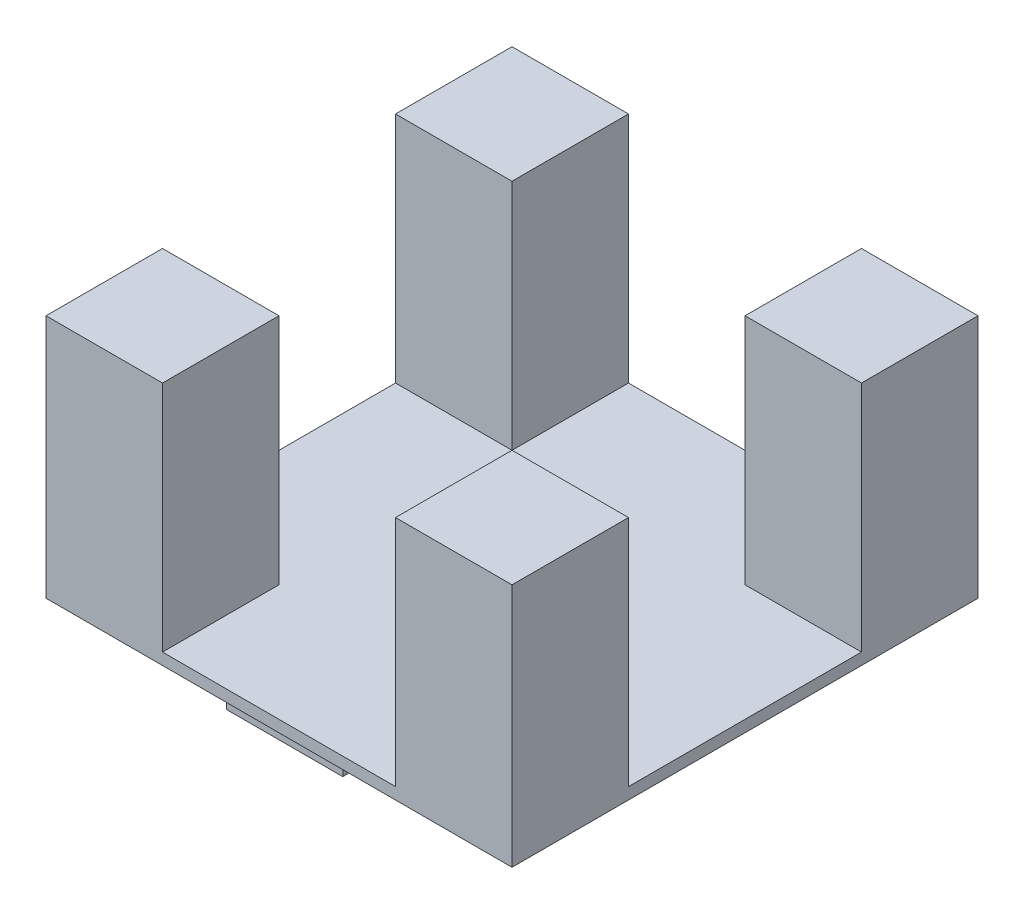
SolidWorks part; units mm, degrees
ref_plane "Front Plane" through (0, 0, 0) normal (0, 0, 1) x (1, 0, 0)
ref_plane "Top Plane" through (0, 0, 0) normal (0, 1, 0) x (1, 0, 0)
ref_plane "Right Plane" through (0, 0, 0) normal (1, 0, 0) x (0, 0, -1)
sketch "Sketch1" plane through (0, 0, 0) normal (0, 1, 0) x (1, 0, 0)
  line L1 (-1000, 1000) -> (1000, 1000)
  line L2 (-1000, 1000) -> (-1000, -1000)
  line L3 (-1000, -1000) -> (1000, -1000)
  line L4 (1000, 1000) -> (1000, -1000)
  line L5 (-1000, 1000) -> (1000, -1000) construction
  line L6 (-1000, -1000) -> (1000, 1000) construction
  point P0 (0, 0)
  dimension "D1" = 2000
  dimension "D2" = 2000
extrude "Boss-Extrude1" add sketch "Sketch1" along normal blind 50
sketch "Sketch2" plane through (0, 50, 0) normal (0, 1, 0) x (1, 0, 0)
  line L1 (-1000, 1000) -> (-500, 1000)
  line L2 (-1000, 1000) -> (-1000, 500)
  line L3 (-1000, 500) -> (-500, 500)
  line L4 (-500, 1000) -> (-500, 500)
  dimension "D1" = 500
  dimension "D2" = 500
extrude "Boss-Extrude2" add sketch "Sketch2" along normal blind 1000
mirror "Mirror1" about plane through (0, 0, 0) normal (0, 0, 1) of "Boss-Extrude2"
mirror "Mirror2" about plane through (0, 0, 0) normal (0, 0, 1) of "Boss-Extrude2" second plane through (0, 0, 0) second plane normal (1, 0, 0)
ref_plane "Plane1" through (-500, 50, 500) normal (0, 0, 1) x (1, 0, 0)
sketch "Sketch4" plane through (0, 0, 0) normal (0, -1, 0) x (1, 0, 0)
  line L0 (0, -577.5) -> (0, 577.5) construction
  line L13 (-250, 976.2432) -> (250, 976.2432)
  line L14 (-250, 976.2432) -> (-250, 476.2432)
  line L15 (-250, 476.2432) -> (250, 476.2432)
  line L16 (250, 976.2432) -> (250, 476.2432)
  line L17 (-250, 976.2432) -> (250, 476.2432) construction
  line L18 (-250, 476.2432) -> (250, 976.2432) construction
  point P0 (0, 726.2432)
  dimension "D1" = 500
  dimension "D2" = 500
extrude "Boss-Extrude4" add sketch "Sketch4" along normal blind 50
